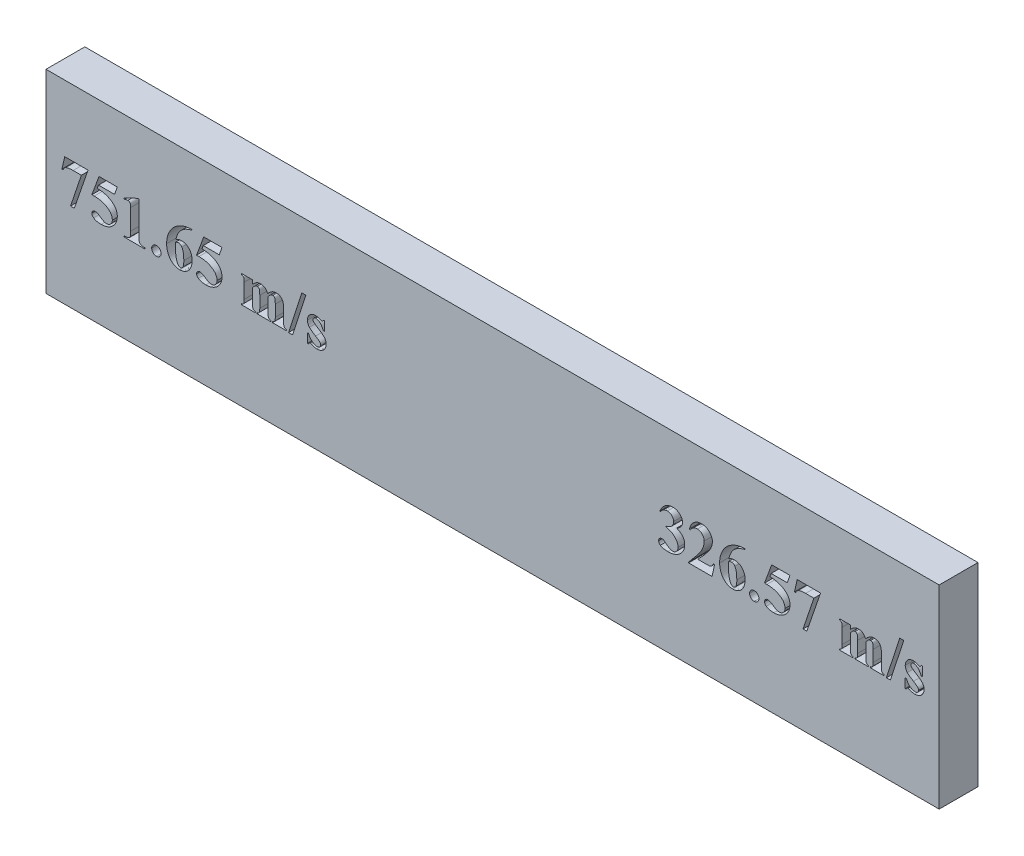
SolidWorks part; units mm, degrees
ref_plane "Alzado" through (0, 0, 0) normal (0, 0, 1) x (1, 0, 0)
ref_plane "Planta" through (0, 0, 0) normal (0, 1, 0) x (1, 0, 0)
ref_plane "Vista lateral" through (0, 0, 0) normal (1, 0, 0) x (0, 0, -1)
sketch "Croquis1" plane through (0, 0, 0) normal (0, 0, 1) x (1, 0, 0)
  line L1 (115, -25) -> (-115, -25)
  line L2 (115, -25) -> (115, 25)
  line L3 (115, 25) -> (-115, 25)
  line L4 (-115, -25) -> (-115, 25)
  line L5 (115, -25) -> (-115, 25) construction
  line L6 (115, 25) -> (-115, -25) construction
  point P0 (0, 0)
  dimension "D1" = 230
  dimension "D2" = 50
extrude "Saliente-Extruir1" add sketch "Croquis1" along normal blind 10
sketch "Croquis3" plane through (0, 0, 10) normal (0, 0, 1) x (1, 0, 0)
  text T0 "<b>751.65 m/s                      326.57 m/s</b>" font "Times New Roman" height in points 42
extrude "Cortar-Extruir1" cut sketch "Croquis3" against normal blind 5
